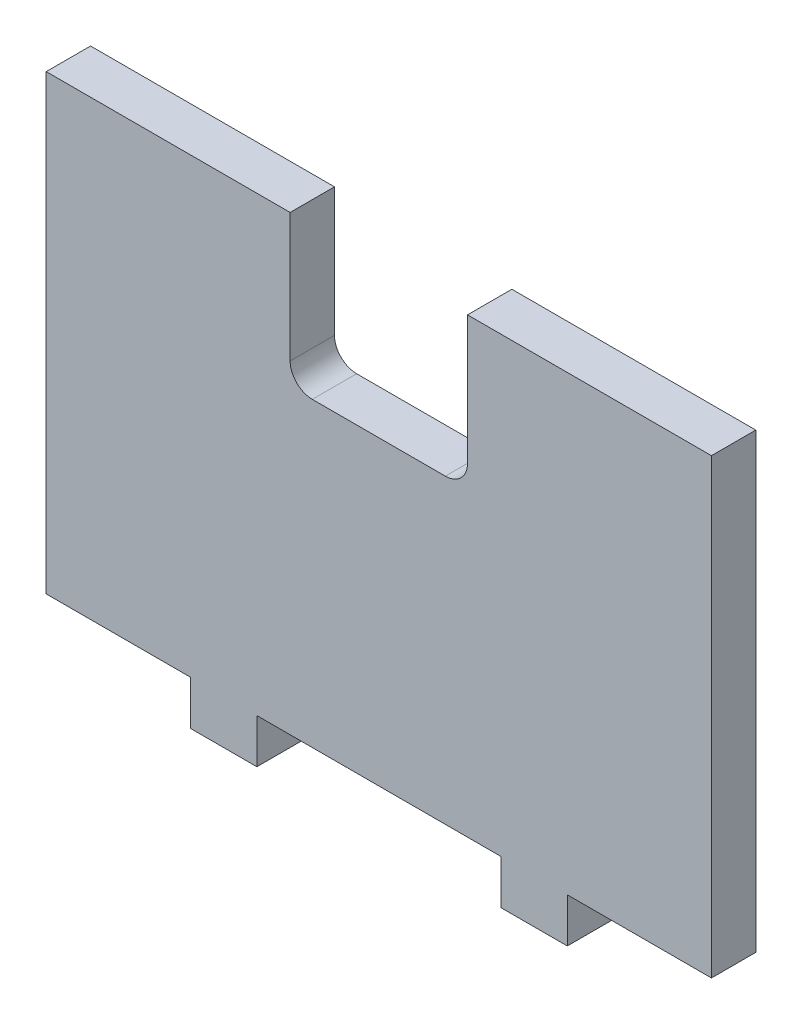
SolidWorks part; units mm, degrees
material "Acrylic (Medium-high impact)"
ref_plane "Front Plane" through (0, 0, 0) normal (0, 0, 1) x (1, 0, 0)
ref_plane "Top Plane" through (0, 0, 0) normal (0, 1, 0) x (1, 0, 0)
ref_plane "Right Plane" through (0, 0, 0) normal (1, 0, 0) x (0, 0, -1)
sketch "Sketch1" plane through (0, 0, 0) normal (0, 0, 1) x (1, 0, 0)
  line L0 (53.975, 0) -> (34.925, 0) construction
  line L1 (-95.25, 142.24) -> (95.25, 142.24)
  line L2 (-95.25, 142.24) -> (-95.25, 12.7)
  line L3 (-95.25, 12.7) -> (-53.975, 12.7)
  line L4 (95.25, 142.24) -> (95.25, 12.7)
  line L5 (53.975, 0) -> (53.975, 12.7) construction
  line L6 (34.925, 0) -> (34.925, 12.7) construction
  line L7 (-34.925, 0) -> (-53.975, 0) construction
  line L8 (-34.925, 0) -> (-34.925, 12.7) construction
  line L9 (-53.975, 0) -> (-53.975, 12.7) construction
  line L10 (53.975, 0) -> (34.925, 0)
  line L11 (53.975, 0) -> (53.975, 12.7)
  line L12 (34.925, 0) -> (34.925, 12.7)
  line L13 (-34.925, 0) -> (-53.975, 0)
  line L14 (-34.925, 0) -> (-34.925, 12.7)
  line L15 (-53.975, 0) -> (-53.975, 12.7)
  line L16 (-34.925, 12.7) -> (34.925, 12.7)
  line L17 (53.975, 12.7) -> (95.25, 12.7)
extrude "Extrude1" add sketch "Sketch1" against normal blind 12.7
sketch "Sketch2" plane through (0, 0, 0) normal (0, 0, 1) x (1, 0, 0)
  line L0 (95.25, 142.24) -> (-95.25, 142.24) construction
  line L1 (-25.4, 142.24) -> (25.4, 142.24)
  line L2 (-25.4, 142.24) -> (-25.4, 99.06)
  line L3 (-25.4, 99.06) -> (25.4, 99.06)
  line L4 (25.4, 142.24) -> (25.4, 99.06)
  point P6 (0, 99.06)
  dimension "D1" = 43.18
  dimension "D2" = 50.8
extrude "Cut-Extrude1" cut sketch "Sketch2" against normal through all
fillet "Fillet1" radius 6.35 2 edges at (25.4, 99.06, -6.35) (-25.4, 99.06, -6.35)
